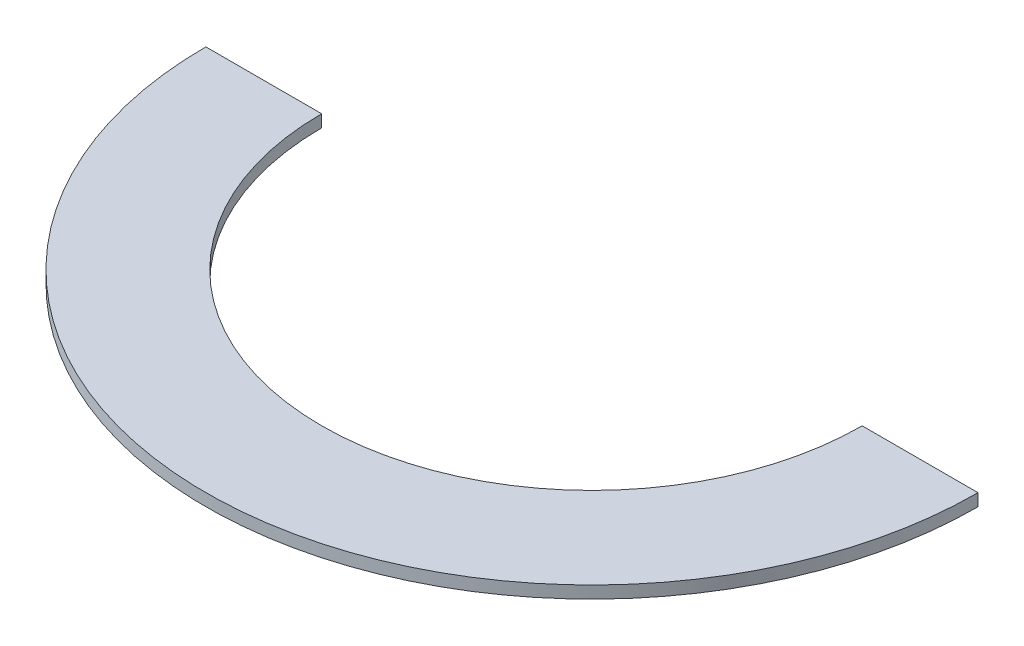
SolidWorks part; units mm, degrees
material "PTFE (general)"
ref_plane "Front Plane" through (0, 0, 0) normal (0, 0, 1) x (1, 0, 0)
ref_plane "Top Plane" through (0, 0, 0) normal (0, 1, 0) x (1, 0, 0)
ref_plane "Right Plane" through (0, 0, 0) normal (1, 0, 0) x (0, 0, -1)
sketch "Sketch1" plane through (0, 0, 0) normal (0, 1, 0) x (1, 0, 0)
  line L0 (-50, 0) -> (-35, 0)
  line L1 (35, 0) -> (50, 0)
  arc A0 (-50, 0) -> (50, 0) centre (0, 0) ccw
  arc A1 (-35, 0) -> (35, 0) centre (0, 0) ccw
  dimension "D1" = 50
  dimension "D2" = 35
extrude "Boss-Extrude1" add sketch "Sketch1" along normal blind 1.5875
